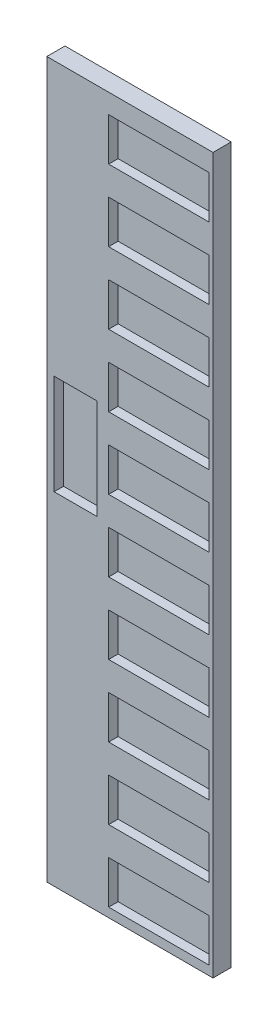
SolidWorks part; units mm, degrees
ref_plane "Front Plane" through (0, 0, 0) normal (0, 0, 1) x (1, 0, 0)
ref_plane "Top Plane" through (0, 0, 0) normal (0, 1, 0) x (1, 0, 0)
ref_plane "Right Plane" through (0, 0, 0) normal (1, 0, 0) x (0, 0, -1)
sketch "Sketch1" plane through (0, 0, 0) normal (0, 0, 1) x (1, 0, 0)
  line L1 (38.1, -250) -> (-38.1, -250)
  line L2 (38.1, -250) -> (38.1, 250)
  line L3 (38.1, 250) -> (-38.1, 250)
  line L4 (-38.1, -250) -> (-38.1, 250)
  line L5 (38.1, -250) -> (-38.1, 250) construction
  line L6 (38.1, 250) -> (-38.1, -250) construction
  point P0 (0, 0)
  dimension "D1" = 76.2
  dimension "D2" = 500
extrude "Boss-Extrude2" add sketch "Sketch1" along normal blind 12.7
sketch "Sketch3" plane through (0, 0, 12.7) normal (0, 0, 1) x (1, 0, 0)
  line L1 (-34.8703, 236.4223) -> (35.1297, 236.4223)
  line L2 (-34.8703, 236.4223) -> (-34.8703, 206.4223)
  line L3 (-34.8703, 206.4223) -> (35.1297, 206.4223)
  line L4 (35.1297, 236.4223) -> (35.1297, 206.4223)
  dimension "D1" = 70
  dimension "D2" = 30
extrude "Cut-Extrude4" cut sketch "Sketch3" against normal blind 6.604
pattern_linear "LPattern1" count 10 spacing 50 along (0, -1, 0) of "Cut-Extrude4"
sketch "Sketch4" plane through (-38.1, 0, 0) normal (-1, 0, 0) x (0, 0, 1)
  line L0 (0, 250) -> (0, -250) construction
  line L1 (0, 250) -> (12.7, 250)
  line L2 (0, 250) -> (0, -250)
  line L3 (0, -250) -> (12.7, -250)
  line L4 (12.7, 250) -> (12.7, -250)
  line L5 (12.7, 250) -> (12.7, -250) construction
extrude "Boss-Extrude4" add sketch "Sketch4" along normal blind 40
sketch "Sketch5" plane through (0, 0, 12.7) normal (0, 0, 1) x (1, 0, 0)
  line L1 (-73.0101, 58.9362) -> (-43.0101, 58.9362)
  line L2 (-73.0101, 58.9362) -> (-73.0101, -11.0638)
  line L3 (-73.0101, -11.0638) -> (-43.0101, -11.0638)
  line L4 (-43.0101, 58.9362) -> (-43.0101, -11.0638)
  dimension "D1" = 30
  dimension "D2" = 70
extrude "Cut-Extrude5" cut sketch "Sketch5" against normal blind 6.604
